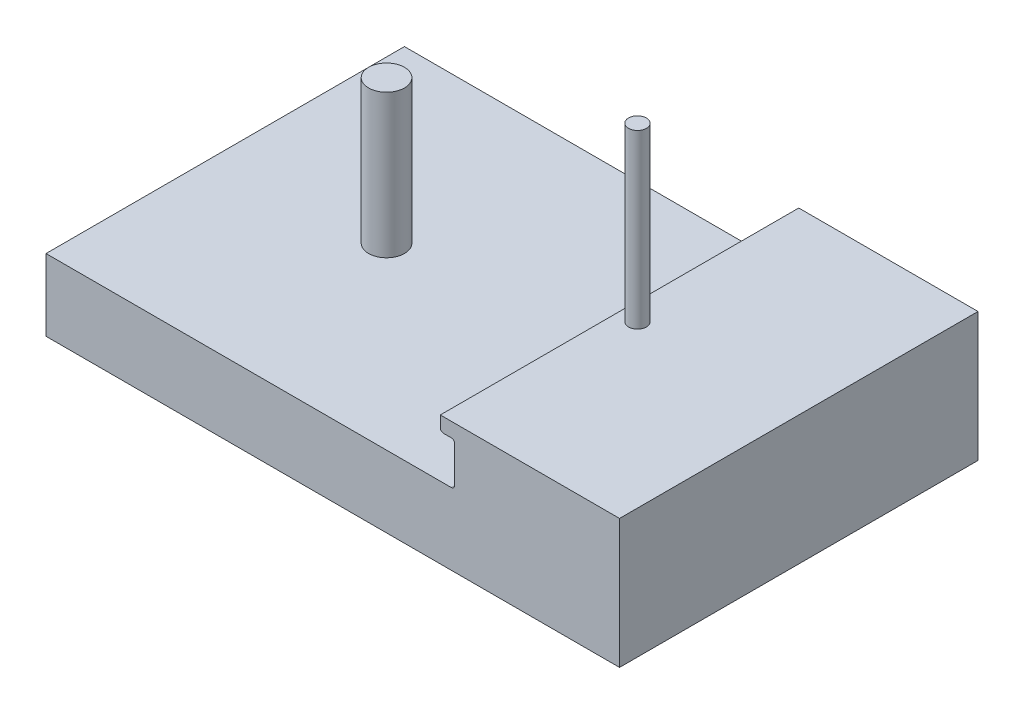
SolidWorks part; units mm, degrees
ref_plane "前基準面" through (0, 0, 0) normal (0, 0, 1) x (1, 0, 0)
ref_plane "上基準面" through (0, 0, 0) normal (0, 1, 0) x (1, 0, 0)
ref_plane "右基準面" through (0, 0, 0) normal (1, 0, 0) x (0, 0, -1)
sketch "草圖1" plane through (0, 0, 0) normal (0, 1, 0) x (1, 0, 0)
  line L1 (-40, 25) -> (40, 25)
  line L2 (-40, 25) -> (-40, -25)
  line L3 (-40, -25) -> (40, -25)
  line L4 (40, 25) -> (40, -25)
  line L5 (-40, 25) -> (40, -25) construction
  line L6 (-40, -25) -> (40, 25) construction
  point P0 (0, 0)
  dimension "D1" = 80
  dimension "D2" = 50
extrude "填料-伸長1" add sketch "草圖1" along normal blind 10
sketch "草圖2" plane through (0, 10, 0) normal (0, 1, 0) x (1, 0, 0)
  line L0 (0, 30.1484) -> (0, -39.0155) construction
  line L1 (-47.9058, 0) -> (82.5066, 0) construction
  circle A0 centre (-17.5, 0) radius 2.5
  circle A1 centre (17.5, 0) radius 1.25
  point P2 (17.3, 0)
  dimension "D1" = 35
  dimension "D2" = 2.5
  dimension "D3" = 5
extrude "填料-伸長2" add sketch "草圖2" along normal blind 20
sketch "草圖4" plane through (0, 10, 0) normal (0, 1, 0) x (1, 0, 0)
  line L0 (-40, -25) -> (40, -25) construction
  line L1 (40, 25) -> (15, 25)
  line L2 (40, 25) -> (40, -25)
  line L3 (40, -25) -> (15, -25)
  line L4 (15, 25) -> (15, -25)
  dimension "D1" = 25
extrude "填料-伸長3" add sketch "草圖4" along normal blind 8
sketch "草圖5" plane through (0, 30, 0) normal (0, 1, 0) x (1, 0, 0)
  circle A1 centre (17.5, 0) radius 1.25
  circle A2 centre (17.5, 0) radius 1.25
  dimension "D1" = 0
extrude "填料-伸長4" add sketch "草圖5" along normal blind 12
sketch "草圖7" plane through (0, 0, -25) normal (0, 0, -1) x (-1, 0, 0)
  line L0 (-15.474, 16) -> (-16.526, 16)
  line L1 (-15, 18) -> (-15, 10) construction
  line L2 (-17, 15.526) -> (-17, 10.474)
  line L3 (-16.526, 10) -> (-15, 10)
  line L4 (-40, 18) -> (-15, 18) construction
  line L5 (-15, 16.474) -> (-15, 18)
  line L6 (-15, 18) -> (-14.5, 18)
  line L7 (-14.5, 18) -> (-14.5, 10)
  line L8 (-15, 10) -> (40, 10) construction
  line L9 (-14.5, 10) -> (-15, 10)
  arc A0 (-16.526, 10) -> (-17, 10.474) centre (-16.526, 10.474) cw
  arc A1 (-17, 15.526) -> (-16.526, 16) centre (-16.526, 15.526) cw
  arc A2 (-15.474, 16) -> (-15, 16.474) centre (-15.474, 16.474) ccw
  point P21 (-15, 16)
  dimension "D3" = 0.474
  dimension "D4" = 0.474
  dimension "D1" = 2.5
  dimension "D2" = 2
  dimension "D5" = 2
extrude "除料-伸長1" cut sketch "草圖7" against normal through all
